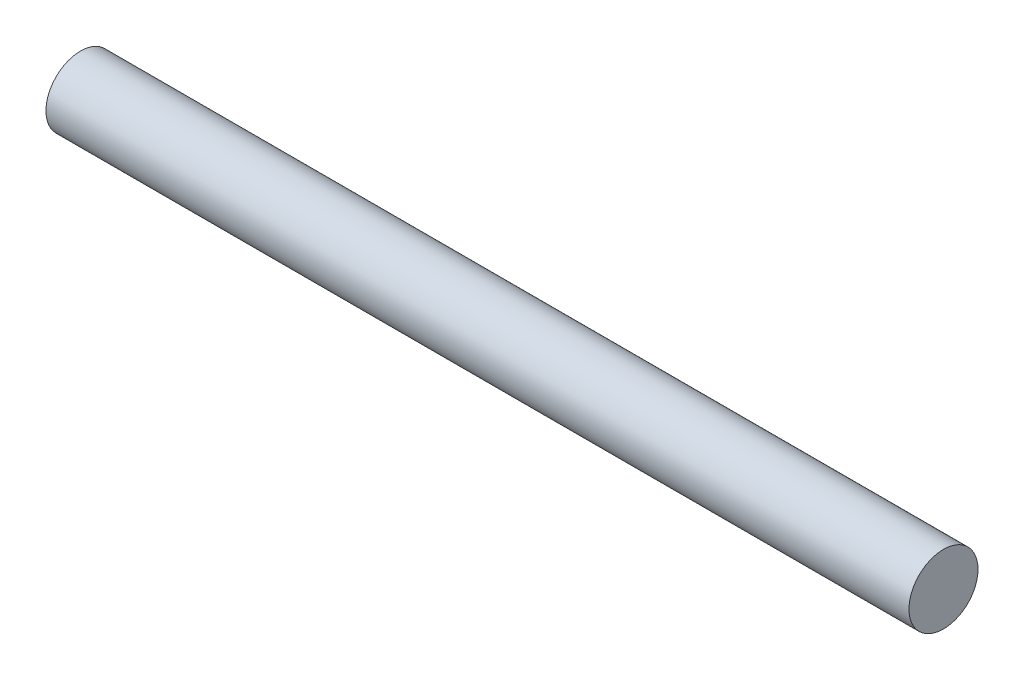
SolidWorks part; units mm, degrees
ref_plane "Front Plane" through (0, 0, 0) normal (0, 0, 1) x (1, 0, 0)
ref_plane "Top Plane" through (0, 0, 0) normal (0, 1, 0) x (1, 0, 0)
ref_plane "Right Plane" through (0, 0, 0) normal (1, 0, 0) x (0, 0, -1)
sketch "Sketch2" plane through (0, 0, 0) normal (1, 0, 0) x (0, 0, -1)
  circle A1 centre (0, 0) radius 4
  dimension "D1" = 8
extrude "Boss-Extrude1" add sketch "Sketch2" along normal blind 100
